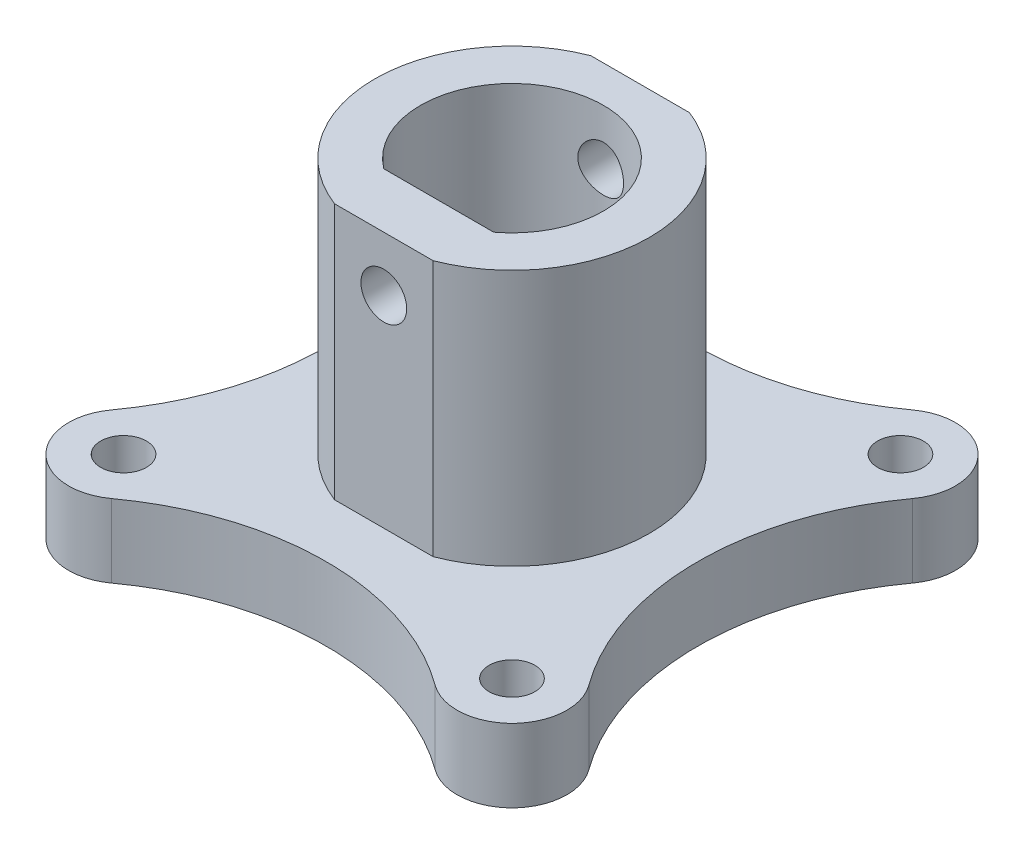
SolidWorks part; units mm, degrees
material "6061 合金"
ref_plane "前视基准面" through (0, 0, 0) normal (0, 0, 1) x (1, 0, 0)
ref_plane "上视基准面" through (0, 0, 0) normal (0, 1, 0) x (1, 0, 0)
ref_plane "右视基准面" through (0, 0, 0) normal (1, 0, 0) x (0, 0, -1)
sketch "草图1" plane through (0, 0, 0) normal (0, 1, 0) x (1, 0, 0)
  line L0 (-3, -4) -> (3, -4)
  arc A0 (-8.8388, 13.0304) -> (-13.0304, 8.8388) centre (-10.6066, 10.6066) ccw
  circle A1 centre (0, 0) radius 15 construction
  arc A2 (-8.8388, 13.0304) -> (8.8388, 13.0304) centre (0, 25.1496) ccw
  arc A3 (13.0304, 8.8388) -> (8.8388, 13.0304) centre (10.6066, 10.6066) ccw
  arc A4 (13.0304, 8.8388) -> (13.0304, -8.8388) centre (25.1496, 0) ccw
  arc A5 (8.8388, -13.0304) -> (13.0304, -8.8388) centre (10.6066, -10.6066) ccw
  arc A6 (8.8388, -13.0304) -> (-8.8388, -13.0304) centre (0, -25.1496) ccw
  arc A7 (-13.0304, -8.8388) -> (-8.8388, -13.0304) centre (-10.6066, -10.6066) ccw
  arc A8 (-13.0304, -8.8388) -> (-13.0304, 8.8388) centre (-25.1496, 0) ccw
  arc A9 (3, -4) -> (-3, -4) centre (0, 0) ccw
  dimension "D2" = 4
  dimension "D1" = 30
  dimension "D3" = 3
  dimension "D4" = 15
  dimension "D5" = 10
  dimension "D6" = 4
extrude "凸台-拉伸1" add sketch "草图1" along normal blind 4
sketch "草图2" plane through (0, 4, 0) normal (0, 1, 0) x (1, 0, 0)
  line L0 (-2.6926, 7) -> (2.6926, 7)
  line L1 (-8.25, 0) -> (8.25, 0) construction
  line L2 (-2.6926, -7) -> (2.6926, -7)
  line L3 (-3, -4) -> (3, -4) construction
  line L4 (-3, -4) -> (3, -4)
  arc A0 (-2.6926, 7) -> (-2.6926, -7) centre (0, 0) ccw
  circle A1 centre (0, 0) radius 5 construction
  arc A2 (3, -4) -> (-3, -4) centre (0, 0) ccw
  arc A3 (2.6926, -7) -> (2.6926, 7) centre (0, 0) ccw
  dimension "D1" = 15
  dimension "D2" = 14
extrude "凸台-拉伸2" add sketch "草图2" along normal blind 14
hole_wizard "M3 螺纹孔1" positions "草图3" profile "草图4" tap size "M3" standard "GB" end condition through all
sketch "草图3" plane through (0, 4, 0) normal (0, 1, 0) x (1, 0, 0)
  point P0 (-10.6066, 10.6066)
  point P3 (10.6066, 10.6066)
  point P6 (10.6066, -10.6066)
  point P9 (-10.6066, -10.6066)
sketch "草图4" plane through (-10.6066, 4, -10.6066) normal (1, 0, 0) x (0, 0, 1)
  line L0 (0, 0) -> (0, 4)
  line L1 (0, 4) -> (1.25, 4)
  line L2 (1.25, 4) -> (1.25, 0)
  line L5 (1.25, 0) -> (0, 0)
  line L11 (0, -6.35) -> (0, 107.95) construction
  dimension "通孔螺纹孔钻头直径" = 2.5
  dimension "通孔螺纹孔钻头深度" = 4
cosmetic thread "孔螺蚊线1" parameters "D2"=3
cosmetic thread "孔螺蚊线2" parameters "D2"=3
cosmetic thread "孔螺蚊线3" parameters "D2"=3
cosmetic thread "孔螺蚊线4" parameters "D2"=3
hole_wizard "M3 螺纹孔2" positions "草图5" profile "草图6" tap size "M3" standard "GB" end condition through all
sketch "草图5" plane through (0, 0, 7) normal (0, 0, 1) x (1, 0, 0)
  line L0 (-2.6926, 18) -> (2.6926, 18) construction
  point P0 (0, 15)
  dimension "D1" = 3
sketch "草图6" plane through (0, 15, 7) normal (1, 0, 0) x (0, -1, 0)
  line L0 (0, 0) -> (0, 20.6066)
  line L1 (0, 20.6066) -> (1.25, 20.6066)
  line L2 (1.25, 20.6066) -> (1.25, 0)
  line L5 (1.25, 0) -> (0, 0)
  line L11 (0, -6.35) -> (0, 107.95) construction
  dimension "通孔螺纹孔钻头直径" = 2.5
  dimension "通孔螺纹孔钻头深度" = 20.6066
cosmetic thread "孔螺蚊线5" parameters "D1"=9, "D2"=3
